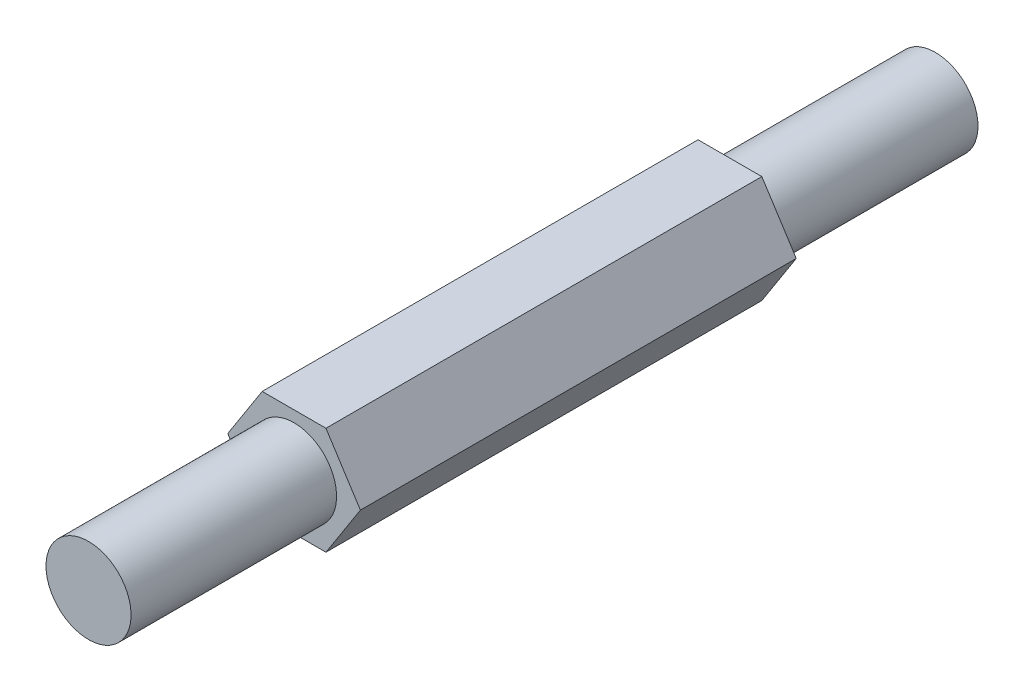
SolidWorks part; units mm, degrees
material "AISI 1015 Steel, Cold Drawn (SS)"
ref_plane "Front Plane" through (0, 0, 0) normal (0, 0, 1) x (1, 0, 0)
ref_plane "Top Plane" through (0, 0, 0) normal (0, 1, 0) x (1, 0, 0)
ref_plane "Right Plane" through (0, 0, 0) normal (1, 0, 0) x (0, 0, -1)
sketch "Sketch1" plane through (0, 0, 0) normal (0, 0, 1) x (1, 0, 0)
  line L4 (-9, 15.1536) -> (9, 15.1536)
  line L5 (9, 15.1536) -> (18.7143, 0)
  line L6 (18.7143, 0) -> (9, -15.1536)
  line L7 (9, -15.1536) -> (-9, -15.1536)
  line L8 (-9, -15.1536) -> (-18.7143, 0)
  line L9 (-18.7143, 0) -> (-9, 15.1536)
  line L10 (-13.8572, 7.5768) -> (13.8572, -7.5768) construction
  line L11 (-13.8572, -7.5768) -> (13.8572, 7.5768) construction
  point P8 (0, 0)
  dimension "D1" = 18
extrude "Boss-Extrude1" add sketch "Sketch1" along normal blind 123
sketch "Sketch2" plane through (0, 0, 0) normal (0, 0, -1) x (-1, 0, 0)
  circle A0 centre (0, 0) radius 12
  dimension "D1" = 24
extrude "Boss-Extrude2" add sketch "Sketch2" along normal blind 58
sketch "Sketch3" plane through (0, 0, 123) normal (0, 0, 1) x (1, 0, 0)
  circle A0 centre (0, 0) radius 12
  dimension "D1" = 24
extrude "Boss-Extrude3" add sketch "Sketch3" along normal blind 58
